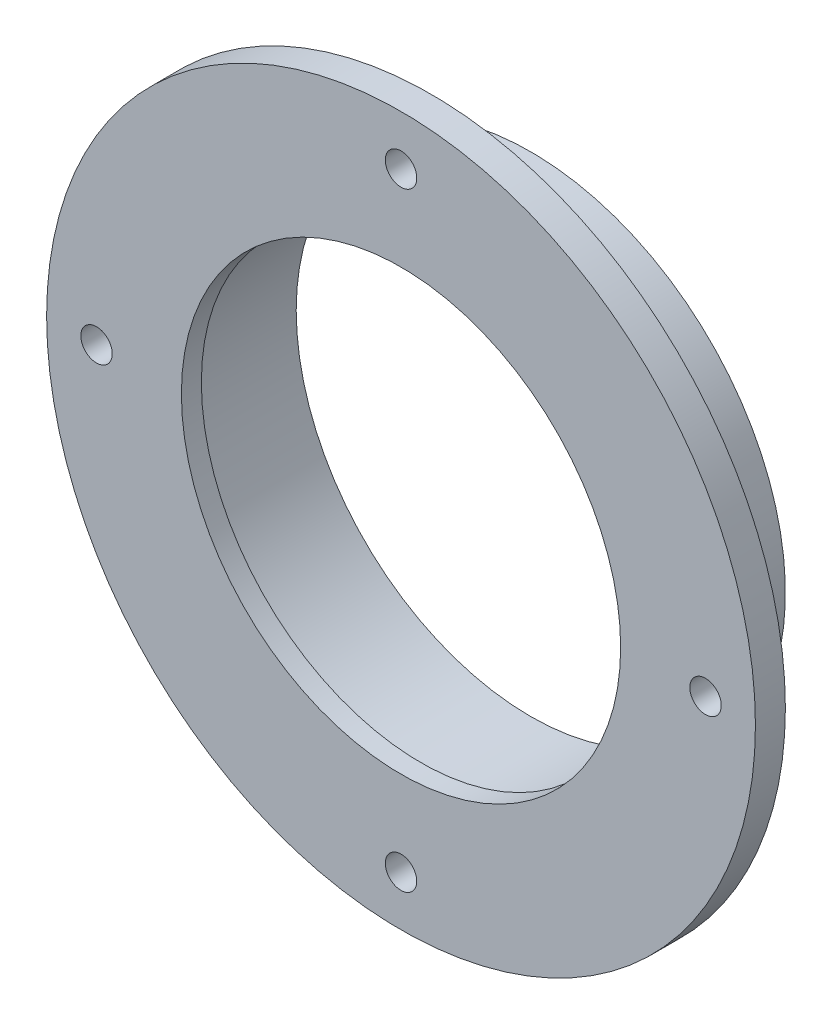
SolidWorks part; units mm, degrees
ref_plane "前视基准面" through (0, 0, 0) normal (0, 0, 1) x (1, 0, 0)
ref_plane "上视基准面" through (0, 0, 0) normal (0, 1, 0) x (1, 0, 0)
ref_plane "右视基准面" through (0, 0, 0) normal (1, 0, 0) x (0, 0, -1)
other "Configuration Table"
sketch "草图1" plane through (0, 0, 0) normal (0, 0, 1) x (1, 0, 0)
  circle A0 centre (0, 0) radius 25.5
  dimension "D1" = 51
extrude "凸台-拉伸1" add sketch "草图1" along normal blind 13
sketch "草图2" plane through (0, 0, 0) normal (0, 0, -1) x (-1, 0, 0)
  circle A0 centre (0, 0) radius 23.5
  dimension "D1" = 47
extrude "切除-拉伸1" cut sketch "草图2" against normal blind 11
sketch "草图3" plane through (0, 0, 13) normal (0, 0, 1) x (1, 0, 0)
  circle A0 centre (0, 0) radius 22
  dimension "D1" = 44
extrude "切除-拉伸2" cut sketch "草图3" against normal blind 2
sketch "草图4" plane through (0, 0, 13) normal (0, 0, 1) x (1, 0, 0)
  circle A0 centre (0, 0) radius 35.5
  circle A2 centre (0, 0) radius 25.5
  dimension "D1" = 71
  dimension "D2" = 51
extrude "凸台-拉伸2" add sketch "草图4" against normal blind 3
sketch "草图5" plane through (0, 0, 13) normal (0, 0, 1) x (1, 0, 0)
  line L0 (0, 0) -> (0, 30.5) construction
  circle A0 centre (0, 30.5) radius 1.575
  circle A1 centre (30.5, 0) radius 1.575
  circle A2 centre (0, -30.5) radius 1.575
  circle A3 centre (-30.5, 0) radius 1.575
  point P13 (0, 0)
  dimension "D1" = 3.15
  dimension "D2" = 30.5
  dimension "D3" = 4
extrude "切除-拉伸3" cut sketch "草图5" against normal through all
